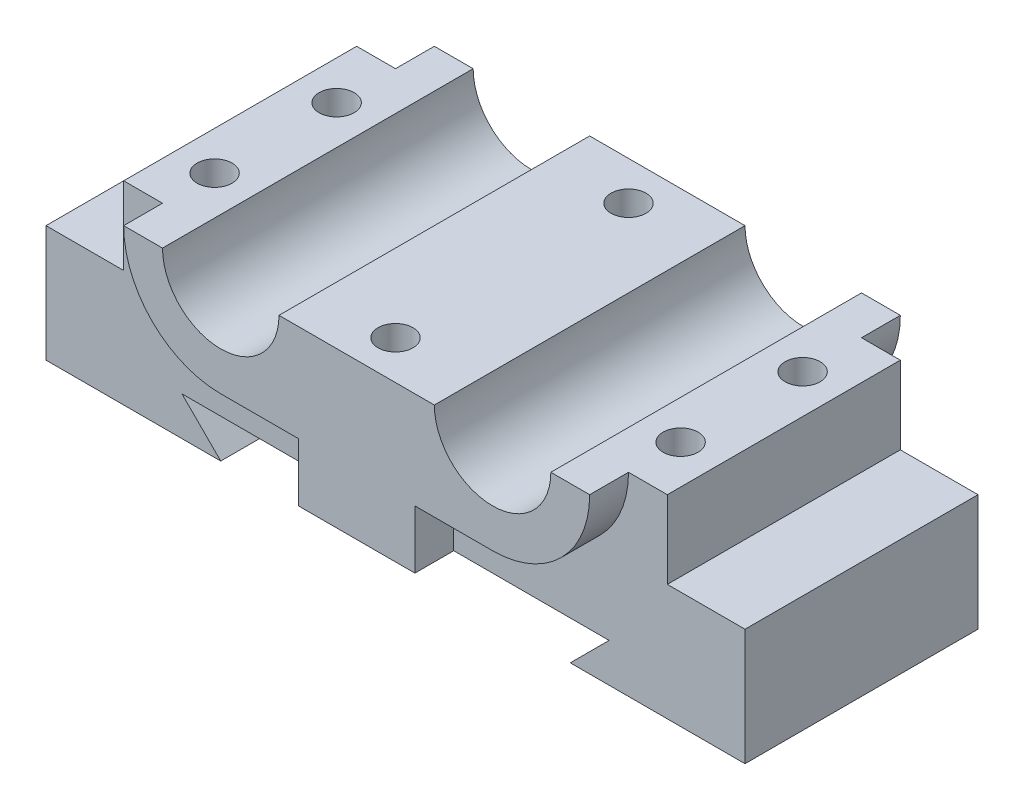
SolidWorks part; units mm, degrees
ref_plane "Front Plane" through (0, 0, 0) normal (0, 0, 1) x (1, 0, 0)
ref_plane "Top Plane" through (0, 0, 0) normal (0, 1, 0) x (1, 0, 0)
ref_plane "Right Plane" through (0, 0, 0) normal (1, 0, 0) x (0, 0, -1)
sketch "Sketch1" plane through (0, 0, 0) normal (0, 0, 1) x (1, 0, 0)
  line L0 (-27.5, -14.3822) -> (27.5, -14.3822)
  line L1 (-35, 5.6178) -> (35, 5.6178)
  line L2 (-45, -4.3822) -> (-45, -19.3822)
  line L3 (-45, -19.3822) -> (-22.5, -19.3822)
  line L4 (45, -4.3822) -> (45, -19.3822)
  line L5 (35, 5.6178) -> (35, -4.3822)
  line L6 (-35, 5.6178) -> (-35, -4.3822)
  line L7 (-45, -4.3822) -> (-35, -4.3822)
  line L8 (35, -4.3822) -> (45, -4.3822)
  line L9 (-22.5, -19.3822) -> (-27.5, -14.3822)
  line L10 (22.5, -19.3822) -> (27.5, -14.3822)
  line L11 (22.5, -19.3822) -> (45, -19.3822)
  line L12 (-45, 5.6178) -> (-45, -19.3822) construction
  line L13 (-45, 5.6178) -> (45, 5.6178) construction
  line L14 (45, 5.6178) -> (45, -19.3822) construction
  line L15 (-35, 5.6178) -> (-35, -19.3822) construction
  line L16 (35, 5.6178) -> (35, -19.3822) construction
  line L18 (-45, -4.3822) -> (45, -4.3822) construction
  point P0 (0, 0)
  point P14 (-103.7256, 35.4323)
  point P15 (45, -14.3822)
  dimension "D1" = 22.5
  dimension "D2" = 45
  dimension "D6" = 27.5
  dimension "D7" = 35
  dimension "D8" = 22.5
  dimension "D9" = 27.5
  dimension "D10" = 25
  dimension "D3" = 10
  dimension "D4" = 10
  dimension "D5" = 10
extrude "Boss-Extrude1" add sketch "Sketch1" against normal blind 30
sketch "Sketch2" plane through (0, 0, 0) normal (0, 0, 1) x (1, 0, 0)
  line L0 (-10, 5.6178) -> (10, 5.6178)
  line L1 (45, -19.3822) -> (45, -4.3822) construction
  line L2 (22.5, -19.3822) -> (45, -19.3822) construction
  line L3 (-7.5, -6.8822) -> (-7.5, -14.3822)
  line L4 (7.5, -6.8822) -> (7.5, -14.3822)
  line L5 (-30, 5.6178) -> (-25, 5.6178)
  line L9 (-17.5, -6.8822) -> (-7.5, -6.8822)
  line L10 (17.5, -6.8822) -> (7.5, -6.8822)
  line L11 (25, 5.6178) -> (30, 5.6178)
  line L15 (-10, 5.6178) -> (10, 5.6178)
  line L16 (-35, -4.3822) -> (-45, -4.3822) construction
  line L17 (-7.5, -14.3822) -> (7.5, -14.3822)
  arc A0 (-25, 5.6178) -> (-10, 5.6178) centre (-17.5, 5.6178) ccw
  arc A1 (-30, 5.6178) -> (-17.5, -6.8822) centre (-17.5, 5.6178) ccw
  arc A2 (30, 5.6178) -> (17.5, -6.8822) centre (17.5, 5.6178) cw
  arc A3 (25, 5.6178) -> (10, 5.6178) centre (17.5, 5.6178) cw
  point P7 (-7.5, 19.3822)
  point P9 (52.1252, -29.0633)
  point P22 (7.5, 19.3822)
  point P23 (46.9556, 5.6178)
  dimension "D3" = 15
  dimension "D4" = 25
  dimension "D2" = 7.5
  dimension "D1" = 10
  dimension "D5" = 15
  dimension "D6" = 62.5
  dimension "D7" = 37.5
  dimension "D8" = 52.5
  dimension "D9" = 5
  dimension "D10" = 15
extrude "Boss-Extrude2" add sketch "Sketch2" along normal blind 5 contours L10 A2 L11 A3 L0 A0 L5 A1 L9 L3 L17 L4
sketch "Sketch3" plane through (0, 0, 5) normal (0, 0, 1) x (1, 0, 0)
  line L0 (-25, 5.6178) -> (-10, 5.6178)
  line L1 (10, 5.6178) -> (25, 5.6178)
  arc A0 (-25, 5.6178) -> (-10, 5.6178) centre (-17.5, 5.6178) ccw
  arc A2 (10, 5.6178) -> (25, 5.6178) centre (17.5, 5.6178) ccw
extrude "Cut-Extrude1" cut sketch "Sketch3" against normal blind 69
sketch "Sketch4" plane through (0, 0, -30) normal (0, 0, -1) x (-1, 0, 0)
  line L0 (-17.5, -6.8822) -> (-7.5, -6.8822)
  line L1 (7.5, -6.8822) -> (17.5, -6.8822)
  line L2 (25, 5.6178) -> (30, 5.6178)
  line L3 (-7.5, -6.8822) -> (-7.5, -14.3822)
  line L4 (7.5, -6.8822) -> (7.5, -14.3822)
  line L5 (-7.5, -14.3822) -> (7.5, -14.3822)
  line L6 (-30, 5.6178) -> (-25, 5.6178)
  line L7 (-10, 5.6178) -> (10, 5.6178)
  line L8 (-45, -19.3822) -> (-45, -4.3822) construction
  line L9 (-22.5, -19.3822) -> (-45, -19.3822) construction
  arc A0 (-30, 5.6178) -> (-17.5, -6.8822) centre (-17.5, 5.6178) ccw
  arc A1 (17.5, -6.8822) -> (30, 5.6178) centre (17.5, 5.6178) ccw
  arc A2 (-25, 5.6178) -> (-10, 5.6178) centre (-17.5, 5.6178) ccw
  arc A3 (10, 5.6178) -> (25, 5.6178) centre (17.5, 5.6178) ccw
  point P13 (-7.5, 0)
  point P15 (7.5, 0)
  dimension "D2" = 25
  dimension "D3" = 7.5
  dimension "D4" = 22.5
  dimension "D5" = 37.5
  dimension "D6" = 52.5
  dimension "D7" = 5
  dimension "D8" = 15
extrude "Boss-Extrude3" add sketch "Sketch4" along normal blind 5
sketch "Sketch7" plane through (0, 5.6178, 0) normal (0, 1, 0) x (1, 0, 0)
  line L0 (-30, 35) -> (-30, 30) construction
  line L1 (-10, 35) -> (10, 35) construction
  line L4 (30, -5) -> (30, 0) construction
  line L5 (-10, -5) -> (10, -5) construction
  circle A0 centre (0, 30) radius 2.25
  circle A1 centre (0, 0) radius 2.25
  dimension "D1" = 4.5
  dimension "D2" = 4.5
  dimension "D3" = 30
  dimension "D4" = 5
  dimension "D5" = 5
  dimension "D6" = 30
extrude "Cut-Extrude3" cut sketch "Sketch7" against normal blind 12.5
sketch "Sketch8" plane through (0, 5.6178, 0) normal (0, 1, 0) x (1, 0, 0)
  line L0 (30, 35) -> (30, 30) construction
  line L1 (30, -5) -> (30, 0) construction
  circle A0 centre (30, 22.4194) radius 2.25
  circle A1 centre (30, 6.7077) radius 2.25
  circle A2 centre (-30, 6.7077) radius 2.25
  circle A3 centre (-30, 22.4194) radius 2.25
  dimension "D1" = 4.5
  dimension "D2" = 4.5
extrude "Cut-Extrude4" cut sketch "Sketch8" against normal blind 12.5
